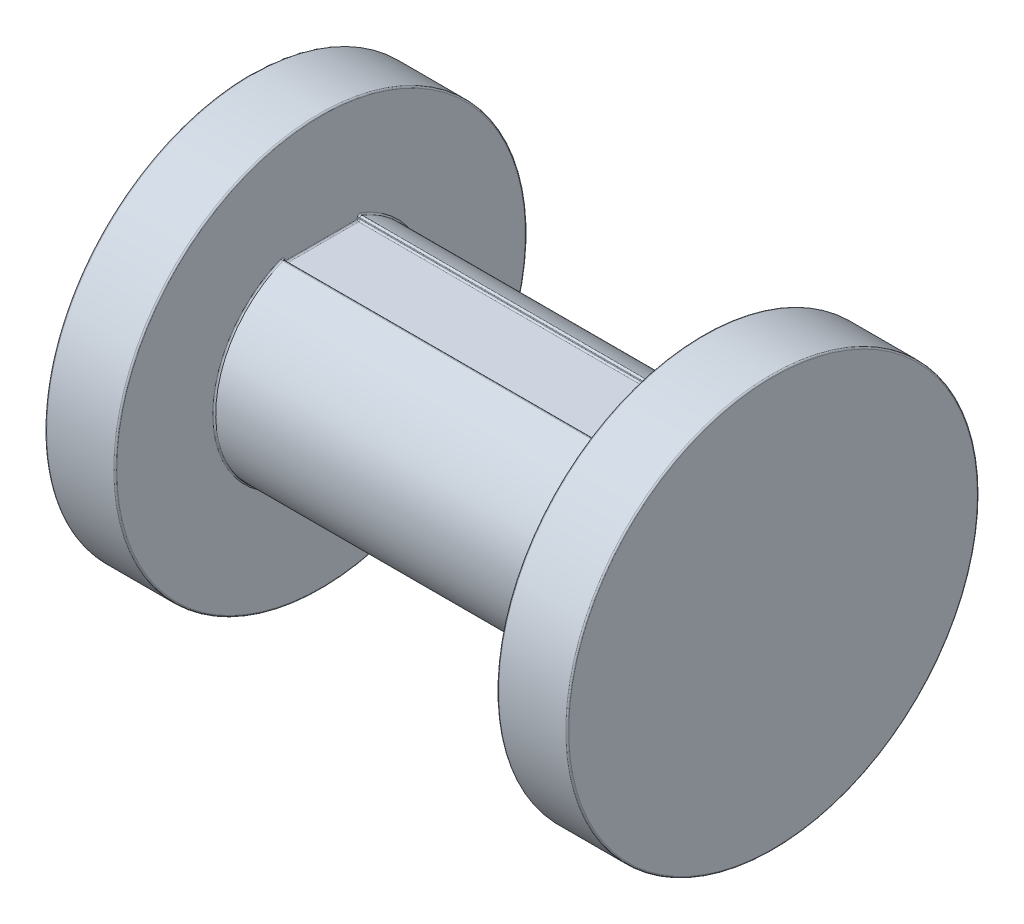
SolidWorks part; units mm, degrees
material "1060 Alloy"
ref_plane "Front Plane" through (0, 0, 0) normal (0, 0, 1) x (1, 0, 0)
ref_plane "Top Plane" through (0, 0, 0) normal (0, 1, 0) x (1, 0, 0)
ref_plane "Right Plane" through (0, 0, 0) normal (1, 0, 0) x (0, 0, -1)
sketch "Sketch4" plane through (0, 0, 0) normal (1, 0, 0) x (0, 0, -1)
  circle A0 centre (0, 0) radius 21.7
  dimension "D1" = 43.4
extrude "Boss-Extrude5" add sketch "Sketch4" along normal mid plane 106.04
sketch "Sketch6" plane through (53.02, 0, 0) normal (1, 0, 0) x (0, 0, -1)
  line L3 (-7.63, 20.3144) -> (-7.63, 19.3464)
  line L4 (-7.63, 19.3464) -> (7.63, 19.3464)
  line L5 (7.63, 19.3464) -> (7.63, 20.3144)
  arc A1 (7.63, 20.3144) -> (-7.63, 20.3144) centre (0, 0) ccw
  circle A2 centre (0, 0) radius 21.7 construction
  point P5 (0, 19.3464)
  dimension "D2" = 19.3464
  dimension "D1" = 15.26
extrude "Cut-Extrude1" cut sketch "Sketch6" against normal through all both and the other way through all
sketch "Sketch5" plane through (53.02, 0, 0) normal (1, 0, 0) x (0, 0, -1)
  circle A0 centre (0, 0) radius 41.8
  dimension "D1" = 83.6
extrude "Boss-Extrude6" add sketch "Sketch5" against normal blind 14.24
mirror "Mirror3" about plane through (0, 0, 0) normal (1, 0, 0) of "Boss-Extrude6"
fillet "Fillet1" radius 0.3 16 edges at (-38.78, 19.3464, 0) (38.78, -21.7, 0) (38.78, 0, -41.8) (53.02, 0, -41.8) (-53.02, 0, -41.8) (-38.78, -21.7, 0) (-38.78, 0, -41.8) (38.78, 19.8304, -7.63) (38.78, 19.8304, 7.63) (-38.78, 19.8304, 7.63) (-38.78, 19.8304, -7.63) (0, 19.3464, 7.63) (0, 19.3464, -7.63) (38.78, 19.3464, 0)
